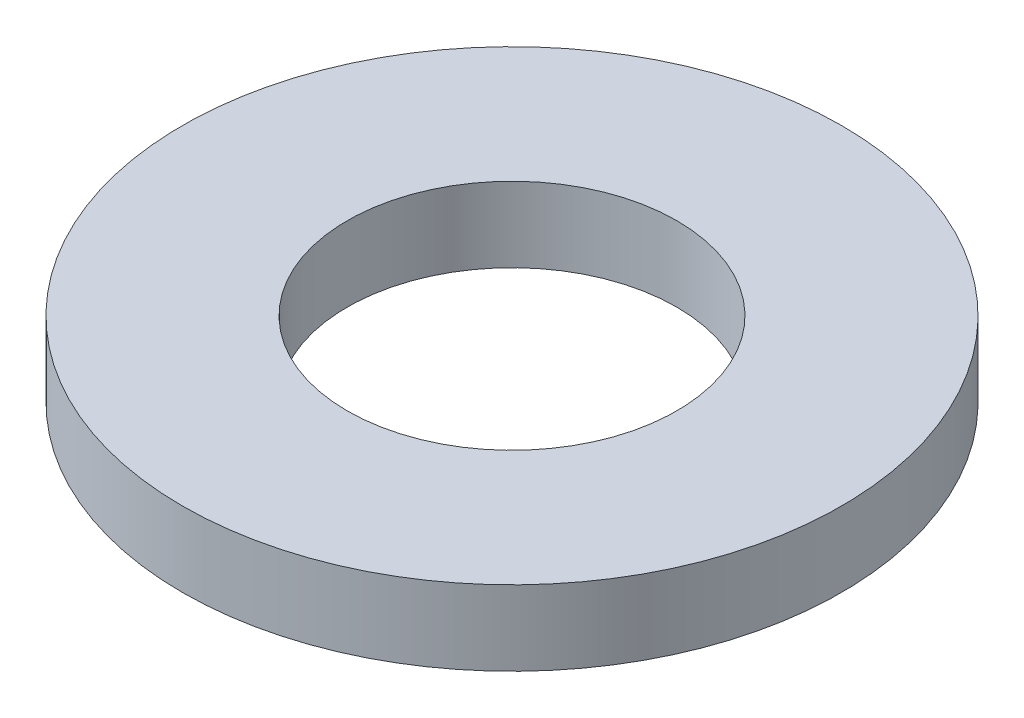
SolidWorks part; units mm, degrees
other "Markup1"
sketch "Sketch2" plane through (110, 12.5, -110) normal (0.5833, 0.4503, -0.676) x (-0.6693, -0.2051, -0.7141)
material "FeSr"
ref_plane "Front Plane" through (0, 0, 0) normal (0, 0, 1) x (1, 0, 0)
ref_plane "Top Plane" through (0, 0, 0) normal (0, 1, 0) x (1, 0, 0)
ref_plane "Right Plane" through (0, 0, 0) normal (1, 0, 0) x (0, 0, -1)
sketch "Sketch1" plane through (0, 0, 0) normal (0, 1, 0) x (1, 0, 0)
  circle A0 centre (0, 0) radius 55
  circle A1 centre (0, 0) radius 110
extrude "Boss-Extrude1" add sketch "Sketch1" along normal mid plane 25
